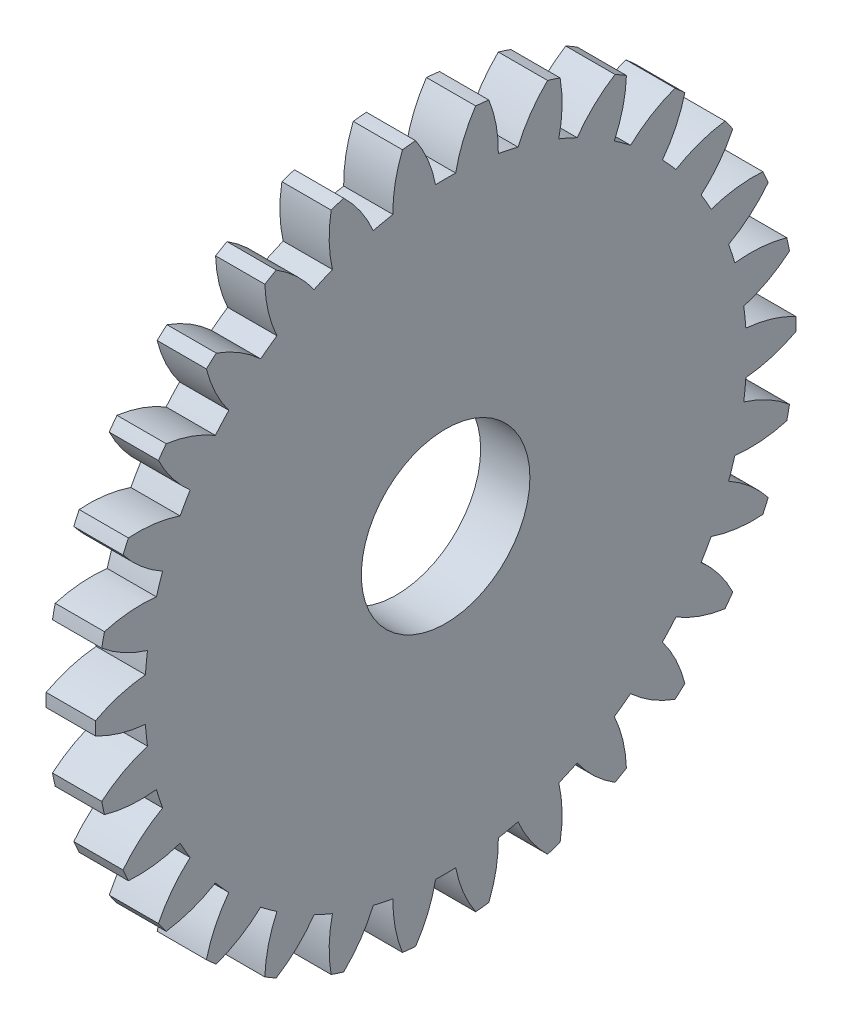
SolidWorks part; units mm, degrees
ref_plane "Plane1" through (0, 0, 0) normal (0, 0, 1) x (1, 0, 0)
ref_plane "Plane2" through (0, 0, 0) normal (0, 1, 0) x (1, 0, 0)
ref_plane "Plane3" through (0, 0, 0) normal (1, 0, 0) x (0, 0, -1)
other "Configuration Table"
sketch "HoldingSke" plane through (0, 0, 0) normal (0, 1, 0) x (1, 0, 0)
  line L0 (0, 0) -> (0.433, -0.25)
  line L1 (-15, 0) -> (100, 0) construction
  line L2 (0, 0) -> (-2.1039, 2.3779)
  line L3 (0, 0) -> (-11.863, 4.5341)
  line L4 (0, 0) -> (7.479, 4.318)
  line L5 (0, 0) -> (-46.8476, -17.4728)
  line L6 (0, 0) -> (-3.7303, -2.5169)
  line L7 (-2.1039, 2.3779) -> (8.6586, 51.2059)
  line L8 (-76.2, 54.61) -> (-74.4, 54.61)
  line L9 (-71.009, 38.7566) -> (-53.1078, 45.2721)
  line L10 (-76.2, 71.12) -> (104.1128, 71.12)
  line L11 (0, 0) -> (-4.5, 0)
  line L12 (-76.2, 101.6) -> (-76.133, 101.6)
  line L13 (24.9733, 27.94) -> (52.9518, 28.4284)
  line L14 (24.9733, 27.94) -> (24.9743, 27.94)
  line L15 (24.9733, 27.94) -> (100.4006, 29.5858)
  line L16 (-63.627, -2) -> (-12.827, -2)
  circle A0 centre (0, 0) radius 5
  circle A1 centre (0, 0) radius 27.499
  circle A2 centre (0, 0) radius 37.5
  circle A3 centre (0, 0) radius 5
  dimension "MHD" = 54.998
  dimension "Hub_dia" = 75
  dimension "Bore" = 10
  dimension "MBD" = 10
  dimension "Num_teeth" = 30
  dimension "Pitch" = 0.5
  dimension "Overall_len" = 50
  dimension "Show_teeth" = 30
  dimension "Thickness" = 4.5
  dimension "OAL" = 50.0001
  dimension "T_dim" = 1.8
  dimension "Ap" = 20
  dimension "H" = 19.05
  dimension "Pitch_radius" = 180.3128
  dimension "Width" = 4.5
  dimension "Backlash" = 0.067
  dimension "Addendum_fac" = 1
  dimension "Dedendum_fac" = 1.25
  dimension "Clearance_fac" = 0.25
  dimension "Dedendum_add" = 0.001
  dimension "Module" = 2
sketch "BasProSke" plane through (0, 0, 0) normal (0, 1, 0) x (1, 0, 0)
  line L0 (-10, 0) -> (60, 0) construction
  line L1 (0, 0) -> (0, 32)
  line L2 (0, 0) -> (4.5, 0)
  line L3 (4.5, 0) -> (4.5, 32)
  line L4 (4.5, 32) -> (0, 32)
  dimension "Thickness" = 4.5
  dimension "Diameter" = 64
revolve "Base-Revolve" add sketch "BasProSke" angle 360 about L0
sketch "TooCutSke" plane through (0, 0, 0) normal (1, 0, 0) x (0, 0, -1)
  line L1 (0, 0) -> (0, 107) construction
  line L2 (0, 0) -> (-1.6873, 29.9525) construction
  line L3 (0, 0) -> (-6.2643, 59.6013) construction
  line L4 (-1.6873, 29.9525) -> (-3.1322, 29.8007) construction
  arc A0 (0.9186, 27.4837) -> (-0.9186, 27.4837) centre (0, 0) ccw
  arc A1 (2.7618, 31.9061) -> (-2.7618, 31.9061) centre (0, 0) ccw
  circle A2 centre (0, 0) radius 30 construction
  circle A3 centre (0, 0) radius 28.1908 construction
  arc A4 (-0.9186, 27.4837) -> (-2.7618, 31.9061) centre (-12.6936, 25.1712) ccw
  arc A5 (2.7618, 31.9061) -> (0.9186, 27.4837) centre (12.6936, 25.1712) ccw
  dimension "Root_dia" = 54.998
  dimension "Overcut_dia" = 64.0508
  dimension "Pitch_dia" = 60
  dimension "Base_dia" = 56.3816
  dimension "Flank_rad" = 12
  dimension "Half_ang" = 6
  dimension "Half_CT" = 1.4528
extrude "ToothCut" cut sketch "TooCutSke" along normal through all
fillet "Breaks" [suppressed] radius 0.04
fillet "RootFillets" [suppressed] radius 0.501
pattern_circular "TeethCuts" count 30 every 12 about axis through (-10, 0, 0) along (1, 0, 0) of "ToothCut", "RootFillets", "Breaks"
sketch "HubNeaOneSke" plane through (0, 0, 0) normal (-1, 0, 0) x (0, 0, 1)
  circle A0 centre (0, 0) radius 27.499
  dimension "Diameter" = 54.998
extrude "HubNearOne" [suppressed] add sketch "HubNeaOneSke" along normal blind 45.5001
sketch "HubNeaBotSke" plane through (0, 0, 0) normal (-1, 0, 0) x (0, 0, 1)
  circle A0 centre (0, 0) radius 27.499
  dimension "Diameter" = 54.998
extrude "HubNearBoth" [suppressed] add sketch "HubNeaBotSke" along normal blind 22.75
ref_plane "FarPln" through (4.5, 0, 0) normal (1, 0, 0) x (0, 0, -1)
sketch "HubFarSke" plane through (4.5, 0, 0) normal (1, 0, 0) x (0, 0, -1)
  circle A0 centre (0, 0) radius 27.499
  dimension "Diameter" = 54.998
extrude "HubFar" [suppressed] add sketch "HubFarSke" along normal blind 22.75
sketch "BorSke" plane through (0, 0, 0) normal (1, 0, 0) x (0, 0, -1)
  circle A0 centre (0, 0) radius 5
  dimension "Diameter" = 10
extrude "Bore" cut sketch "BorSke" along normal mid plane 100.0001
sketch "KeySke" plane through (0, 0, 0) normal (1, 0, 0) x (0, 0, -1)
  line L0 (-2, 0) -> (-2, 6.8)
  line L1 (-2, 6.8) -> (2, 6.8)
  line L2 (2, 6.8) -> (2, 0)
  line L3 (0, 0) -> (0, 34) construction
  line L4 (-2, 0) -> (2, 0)
  dimension "Offset" = 6.8
  dimension "Width" = 4
extrude "Keyway" [suppressed] cut sketch "KeySke" along normal mid plane 100.0001
pattern_circular "Keyway2" [suppressed] count 2 every 90 about axis through (-10, 0, 0) along (1, 0, 0)
sketch "Sketch1" plane through (4.5, 0, 0) normal (1, 0, 0) x (0, 0, -1)
  circle A0 centre (0, 0) radius 7.7
  arc A120 (-31.9943, -0.6021) -> (-27.4291, -1.9593) centre (-26.3602, 9.993) ccw
  arc A121 (-27.4291, -1.9593) -> (-27.2371, -3.7863) centre (0, 0) ccw
  arc A122 (-27.2371, -3.7863) -> (-31.4204, -6.063) centre (-23.7065, -15.2552) ccw
  arc A123 (-31.4204, -6.063) -> (-31.17, -7.241) centre (0, 0) ccw
  arc A124 (-31.17, -7.241) -> (-26.4224, -7.6193) centre (-27.8618, 4.294) ccw
  arc A125 (-26.4224, -7.6193) -> (-25.8547, -9.3665) centre (0, 0) ccw
  arc A126 (-25.8547, -9.3665) -> (-29.4732, -12.4632) centre (-20.0167, -19.8507) ccw
  arc A127 (-29.4732, -12.4632) -> (-28.9834, -13.5633) centre (0, 0) ccw
  arc A128 (-28.9834, -13.5633) -> (-24.2608, -12.9463) centre (-28.1458, -1.5926) ccw
  arc A129 (-24.2608, -12.9463) -> (-23.3423, -14.5373) centre (0, 0) ccw
  arc A130 (-23.3423, -14.5373) -> (-26.2379, -18.3187) centre (-15.4521, -23.5786) ccw
  arc A131 (-26.2379, -18.3187) -> (-25.53, -19.2929) centre (0, 0) ccw
  arc A132 (-25.53, -19.2929) -> (-21.039, -17.7075) centre (-27.1996, -7.4096) ccw
  arc A133 (-21.039, -17.7075) -> (-19.8097, -19.0728) centre (0, 0) ccw
  arc A134 (-19.8097, -19.0728) -> (-21.8559, -23.3735) centre (-10.2122, -26.2761) ccw
  arc A135 (-21.8559, -23.3735) -> (-20.9609, -24.1793) centre (0, 0) ccw
  arc A136 (-20.9609, -24.1793) -> (-16.8976, -21.6948) centre (-25.0647, -12.9028) ccw
  arc A137 (-16.8976, -21.6948) -> (-15.4114, -22.7747) centre (0, 0) ccw
  arc A138 (-15.4114, -22.7747) -> (-16.5186, -27.4068) centre (-4.5259, -27.8251) ccw
  arc A139 (-16.5186, -27.4068) -> (-15.4757, -28.009) centre (0, 0) ccw
  arc A140 (-15.4757, -28.009) -> (-12.0177, -24.734) centre (-21.8343, -17.8321) ccw
  arc A141 (-12.0177, -24.734) -> (-10.3395, -25.4812) centre (0, 0) ccw
  arc A142 (-10.3395, -25.4812) -> (-10.4594, -30.2424) centre (1.3582, -28.158) ccw
  arc A143 (-10.4594, -30.2424) -> (-9.3141, -30.6145) centre (0, 0) ccw
  arc A144 (-9.3141, -30.6145) -> (-6.6127, -26.6921) centre (-17.6497, -21.982) ccw
  arc A145 (-6.6127, -26.6921) -> (-4.8157, -27.074) centre (0, 0) ccw
  arc A146 (-4.8157, -27.074) -> (-3.9431, -31.7561) centre (7.1829, -27.2603) ccw
  arc A147 (-3.9431, -31.7561) -> (-2.7455, -31.882) centre (0, 0) ccw
  arc A148 (-2.7455, -31.882) -> (-0.9186, -27.4837) centre (-12.6936, -25.1712) ccw
  arc A149 (-0.9186, -27.4837) -> (0.9186, -27.4837) centre (0, 0) ccw
  arc A150 (0.9186, -27.4837) -> (2.7455, -31.882) centre (12.6936, -25.1712) ccw
  arc A151 (2.7455, -31.882) -> (3.9431, -31.7561) centre (0, 0) ccw
  arc A152 (3.9431, -31.7561) -> (4.8157, -27.074) centre (-7.1829, -27.2603) ccw
  arc A153 (4.8157, -27.074) -> (6.6127, -26.6921) centre (0, 0) ccw
  arc A154 (6.6127, -26.6921) -> (9.3141, -30.6145) centre (17.6497, -21.982) ccw
  arc A155 (9.3141, -30.6145) -> (10.4594, -30.2424) centre (0, 0) ccw
  arc A156 (10.4594, -30.2424) -> (10.3395, -25.4812) centre (-1.3582, -28.158) ccw
  arc A157 (10.3395, -25.4812) -> (12.0177, -24.734) centre (0, 0) ccw
  arc A158 (12.0177, -24.734) -> (15.4757, -28.009) centre (21.8343, -17.8321) ccw
  arc A159 (15.4757, -28.009) -> (16.5186, -27.4068) centre (0, 0) ccw
  arc A160 (16.5186, -27.4068) -> (15.4114, -22.7747) centre (4.5259, -27.8251) ccw
  arc A161 (15.4114, -22.7747) -> (16.8976, -21.6948) centre (0, 0) ccw
  arc A162 (16.8976, -21.6948) -> (20.9609, -24.1793) centre (25.0647, -12.9028) ccw
  arc A163 (20.9609, -24.1793) -> (21.8559, -23.3735) centre (0, 0) ccw
  arc A164 (21.8559, -23.3735) -> (19.8097, -19.0728) centre (10.2122, -26.2761) ccw
  arc A165 (19.8097, -19.0728) -> (21.039, -17.7075) centre (0, 0) ccw
  arc A166 (21.039, -17.7075) -> (25.53, -19.2929) centre (27.1996, -7.4096) ccw
  arc A167 (25.53, -19.2929) -> (26.2379, -18.3187) centre (0, 0) ccw
  arc A168 (26.2379, -18.3187) -> (23.3423, -14.5373) centre (15.4521, -23.5786) ccw
  arc A169 (23.3423, -14.5373) -> (24.2608, -12.9463) centre (0, 0) ccw
  arc A170 (24.2608, -12.9463) -> (28.9834, -13.5633) centre (28.1458, -1.5926) ccw
  arc A171 (28.9834, -13.5633) -> (29.4732, -12.4632) centre (0, 0) ccw
  arc A172 (29.4732, -12.4632) -> (25.8547, -9.3665) centre (20.0167, -19.8507) ccw
  arc A173 (25.8547, -9.3665) -> (26.4224, -7.6193) centre (0, 0) ccw
  arc A174 (26.4224, -7.6193) -> (31.17, -7.241) centre (27.8618, 4.294) ccw
  arc A175 (31.17, -7.241) -> (31.4204, -6.063) centre (0, 0) ccw
  arc A176 (31.4204, -6.063) -> (27.2371, -3.7863) centre (23.7065, -15.2552) ccw
  arc A177 (27.2371, -3.7863) -> (27.4291, -1.9593) centre (0, 0) ccw
  arc A178 (27.4291, -1.9593) -> (31.9943, -0.6021) centre (26.3602, 9.993) ccw
  arc A179 (31.9943, -0.6021) -> (31.9943, 0.6021) centre (0, 0) ccw
  arc A180 (31.9943, 0.6021) -> (27.4291, 1.9593) centre (26.3602, -9.993) ccw
  arc A181 (27.4291, 1.9593) -> (27.2371, 3.7863) centre (0, 0) ccw
  arc A182 (27.2371, 3.7863) -> (31.4204, 6.063) centre (23.7065, 15.2552) ccw
  arc A183 (31.4204, 6.063) -> (31.17, 7.241) centre (0, 0) ccw
  arc A184 (31.17, 7.241) -> (26.4224, 7.6193) centre (27.8618, -4.294) ccw
  arc A185 (26.4224, 7.6193) -> (25.8547, 9.3665) centre (0, 0) ccw
  arc A186 (25.8547, 9.3665) -> (29.4732, 12.4632) centre (20.0167, 19.8507) ccw
  arc A187 (29.4732, 12.4632) -> (28.9834, 13.5633) centre (0, 0) ccw
  arc A188 (28.9834, 13.5633) -> (24.2608, 12.9463) centre (28.1458, 1.5926) ccw
  arc A189 (24.2608, 12.9463) -> (23.3423, 14.5373) centre (0, 0) ccw
  arc A190 (23.3423, 14.5373) -> (26.2379, 18.3187) centre (15.4521, 23.5786) ccw
  arc A191 (26.2379, 18.3187) -> (25.53, 19.2929) centre (0, 0) ccw
  arc A192 (25.53, 19.2929) -> (21.039, 17.7075) centre (27.1996, 7.4096) ccw
  arc A193 (21.039, 17.7075) -> (19.8097, 19.0728) centre (0, 0) ccw
  arc A194 (19.8097, 19.0728) -> (21.8559, 23.3735) centre (10.2122, 26.2761) ccw
  arc A195 (21.8559, 23.3735) -> (20.9609, 24.1793) centre (0, 0) ccw
  arc A196 (20.9609, 24.1793) -> (16.8976, 21.6948) centre (25.0647, 12.9028) ccw
  arc A197 (16.8976, 21.6948) -> (15.4114, 22.7747) centre (0, 0) ccw
  arc A198 (15.4114, 22.7747) -> (16.5186, 27.4068) centre (4.5259, 27.8251) ccw
  arc A199 (16.5186, 27.4068) -> (15.4757, 28.009) centre (0, 0) ccw
  arc A200 (15.4757, 28.009) -> (12.0177, 24.734) centre (21.8343, 17.8321) ccw
  arc A201 (12.0177, 24.734) -> (10.3395, 25.4812) centre (0, 0) ccw
  arc A202 (10.3395, 25.4812) -> (10.4594, 30.2424) centre (-1.3582, 28.158) ccw
  arc A203 (10.4594, 30.2424) -> (9.3141, 30.6145) centre (0, 0) ccw
  arc A204 (9.3141, 30.6145) -> (6.6127, 26.6921) centre (17.6497, 21.982) ccw
  arc A205 (6.6127, 26.6921) -> (4.8157, 27.074) centre (0, 0) ccw
  arc A206 (4.8157, 27.074) -> (3.9431, 31.7561) centre (-7.1829, 27.2603) ccw
  arc A207 (3.9431, 31.7561) -> (2.7455, 31.882) centre (0, 0) ccw
  arc A208 (2.7455, 31.882) -> (0.9186, 27.4837) centre (12.6936, 25.1712) ccw
  arc A209 (0.9186, 27.4837) -> (-0.9186, 27.4837) centre (0, 0) ccw
  arc A210 (-0.9186, 27.4837) -> (-2.7455, 31.882) centre (-12.6936, 25.1712) ccw
  arc A211 (-2.7455, 31.882) -> (-3.9431, 31.7561) centre (0, 0) ccw
  arc A212 (-3.9431, 31.7561) -> (-4.8157, 27.074) centre (7.1829, 27.2603) ccw
  arc A213 (-4.8157, 27.074) -> (-6.6127, 26.6921) centre (0, 0) ccw
  arc A214 (-6.6127, 26.6921) -> (-9.3141, 30.6145) centre (-17.6497, 21.982) ccw
  arc A215 (-9.3141, 30.6145) -> (-10.4594, 30.2424) centre (0, 0) ccw
  arc A216 (-10.4594, 30.2424) -> (-10.3395, 25.4812) centre (1.3582, 28.158) ccw
  arc A217 (-10.3395, 25.4812) -> (-12.0177, 24.734) centre (0, 0) ccw
  arc A218 (-12.0177, 24.734) -> (-15.4757, 28.009) centre (-21.8343, 17.8321) ccw
  arc A219 (-15.4757, 28.009) -> (-16.5186, 27.4068) centre (0, 0) ccw
  arc A220 (-16.5186, 27.4068) -> (-15.4114, 22.7747) centre (-4.5259, 27.8251) ccw
  arc A221 (-15.4114, 22.7747) -> (-16.8976, 21.6948) centre (0, 0) ccw
  arc A222 (-16.8976, 21.6948) -> (-20.9609, 24.1793) centre (-25.0647, 12.9028) ccw
  arc A223 (-20.9609, 24.1793) -> (-21.8559, 23.3735) centre (0, 0) ccw
  arc A224 (-21.8559, 23.3735) -> (-19.8097, 19.0728) centre (-10.2122, 26.2761) ccw
  arc A225 (-19.8097, 19.0728) -> (-21.039, 17.7075) centre (0, 0) ccw
  arc A226 (-21.039, 17.7075) -> (-25.53, 19.2929) centre (-27.1996, 7.4096) ccw
  arc A227 (-25.53, 19.2929) -> (-26.2379, 18.3187) centre (0, 0) ccw
  arc A228 (-26.2379, 18.3187) -> (-23.3423, 14.5373) centre (-15.4521, 23.5786) ccw
  arc A229 (-23.3423, 14.5373) -> (-24.2608, 12.9463) centre (0, 0) ccw
  arc A230 (-24.2608, 12.9463) -> (-28.9834, 13.5633) centre (-28.1458, 1.5926) ccw
  arc A231 (-28.9834, 13.5633) -> (-29.4732, 12.4632) centre (0, 0) ccw
  arc A232 (-29.4732, 12.4632) -> (-25.8547, 9.3665) centre (-20.0167, 19.8507) ccw
  arc A233 (-25.8547, 9.3665) -> (-26.4224, 7.6193) centre (0, 0) ccw
  arc A234 (-26.4224, 7.6193) -> (-31.17, 7.241) centre (-27.8618, -4.294) ccw
  arc A235 (-31.17, 7.241) -> (-31.4204, 6.063) centre (0, 0) ccw
  arc A236 (-31.4204, 6.063) -> (-27.2371, 3.7863) centre (-23.7065, 15.2552) ccw
  arc A237 (-27.2371, 3.7863) -> (-27.4291, 1.9593) centre (0, 0) ccw
  arc A238 (-27.4291, 1.9593) -> (-31.9943, 0.6021) centre (-26.3602, -9.993) ccw
  arc A239 (-31.9943, 0.6021) -> (-31.9943, -0.6021) centre (0, 0) ccw
  arc A240 (-31.9943, -0.6021) -> (-27.4291, -1.9593) centre (-26.3602, 9.993) ccw
  arc A241 (-27.4291, -1.9593) -> (-27.2371, -3.7863) centre (0, 0) ccw
  arc A242 (-27.2371, -3.7863) -> (-31.4204, -6.063) centre (-23.7065, -15.2552) ccw
  arc A243 (-31.4204, -6.063) -> (-31.17, -7.241) centre (0, 0) ccw
  arc A244 (-31.17, -7.241) -> (-26.4224, -7.6193) centre (-27.8618, 4.294) ccw
  arc A245 (-26.4224, -7.6193) -> (-25.8547, -9.3665) centre (0, 0) ccw
  arc A246 (-25.8547, -9.3665) -> (-29.4732, -12.4632) centre (-20.0167, -19.8507) ccw
  arc A247 (-29.4732, -12.4632) -> (-28.9834, -13.5633) centre (0, 0) ccw
  arc A248 (-28.9834, -13.5633) -> (-24.2608, -12.9463) centre (-28.1458, -1.5926) ccw
  arc A249 (-24.2608, -12.9463) -> (-23.3423, -14.5373) centre (0, 0) ccw
  arc A250 (-23.3423, -14.5373) -> (-26.2379, -18.3187) centre (-15.4521, -23.5786) ccw
  arc A251 (-26.2379, -18.3187) -> (-25.53, -19.2929) centre (0, 0) ccw
  arc A252 (-25.53, -19.2929) -> (-21.039, -17.7075) centre (-27.1996, -7.4096) ccw
  arc A253 (-21.039, -17.7075) -> (-19.8097, -19.0728) centre (0, 0) ccw
  arc A254 (-19.8097, -19.0728) -> (-21.8559, -23.3735) centre (-10.2122, -26.2761) ccw
  arc A255 (-21.8559, -23.3735) -> (-20.9609, -24.1793) centre (0, 0) ccw
  arc A256 (-20.9609, -24.1793) -> (-16.8976, -21.6948) centre (-25.0647, -12.9028) ccw
  arc A257 (-16.8976, -21.6948) -> (-15.4114, -22.7747) centre (0, 0) ccw
  arc A258 (-15.4114, -22.7747) -> (-16.5186, -27.4068) centre (-4.5259, -27.8251) ccw
  arc A259 (-16.5186, -27.4068) -> (-15.4757, -28.009) centre (0, 0) ccw
  arc A260 (-15.4757, -28.009) -> (-12.0177, -24.734) centre (-21.8343, -17.8321) ccw
  arc A261 (-12.0177, -24.734) -> (-10.3395, -25.4812) centre (0, 0) ccw
  arc A262 (-10.3395, -25.4812) -> (-10.4594, -30.2424) centre (1.3582, -28.158) ccw
  arc A263 (-10.4594, -30.2424) -> (-9.3141, -30.6145) centre (0, 0) ccw
  arc A264 (-9.3141, -30.6145) -> (-6.6127, -26.6921) centre (-17.6497, -21.982) ccw
  arc A265 (-6.6127, -26.6921) -> (-4.8157, -27.074) centre (0, 0) ccw
  arc A266 (-4.8157, -27.074) -> (-3.9431, -31.7561) centre (7.1829, -27.2603) ccw
  arc A267 (-3.9431, -31.7561) -> (-2.7455, -31.882) centre (0, 0) ccw
  arc A268 (-2.7455, -31.882) -> (-0.9186, -27.4837) centre (-12.6936, -25.1712) ccw
  arc A269 (-0.9186, -27.4837) -> (0.9186, -27.4837) centre (0, 0) ccw
  arc A270 (0.9186, -27.4837) -> (2.7455, -31.882) centre (12.6936, -25.1712) ccw
  arc A271 (2.7455, -31.882) -> (3.9431, -31.7561) centre (0, 0) ccw
  arc A272 (3.9431, -31.7561) -> (4.8157, -27.074) centre (-7.1829, -27.2603) ccw
  arc A273 (4.8157, -27.074) -> (6.6127, -26.6921) centre (0, 0) ccw
  arc A274 (6.6127, -26.6921) -> (9.3141, -30.6145) centre (17.6497, -21.982) ccw
  arc A275 (9.3141, -30.6145) -> (10.4594, -30.2424) centre (0, 0) ccw
  arc A276 (10.4594, -30.2424) -> (10.3395, -25.4812) centre (-1.3582, -28.158) ccw
  arc A277 (10.3395, -25.4812) -> (12.0177, -24.734) centre (0, 0) ccw
  arc A278 (12.0177, -24.734) -> (15.4757, -28.009) centre (21.8343, -17.8321) ccw
  arc A279 (15.4757, -28.009) -> (16.5186, -27.4068) centre (0, 0) ccw
  arc A280 (16.5186, -27.4068) -> (15.4114, -22.7747) centre (4.5259, -27.8251) ccw
  arc A281 (15.4114, -22.7747) -> (16.8976, -21.6948) centre (0, 0) ccw
  arc A282 (16.8976, -21.6948) -> (20.9609, -24.1793) centre (25.0647, -12.9028) ccw
  arc A283 (20.9609, -24.1793) -> (21.8559, -23.3735) centre (0, 0) ccw
  arc A284 (21.8559, -23.3735) -> (19.8097, -19.0728) centre (10.2122, -26.2761) ccw
  arc A285 (19.8097, -19.0728) -> (21.039, -17.7075) centre (0, 0) ccw
  arc A286 (21.039, -17.7075) -> (25.53, -19.2929) centre (27.1996, -7.4096) ccw
  arc A287 (25.53, -19.2929) -> (26.2379, -18.3187) centre (0, 0) ccw
  arc A288 (26.2379, -18.3187) -> (23.3423, -14.5373) centre (15.4521, -23.5786) ccw
  arc A289 (23.3423, -14.5373) -> (24.2608, -12.9463) centre (0, 0) ccw
  arc A290 (24.2608, -12.9463) -> (28.9834, -13.5633) centre (28.1458, -1.5926) ccw
  arc A291 (28.9834, -13.5633) -> (29.4732, -12.4632) centre (0, 0) ccw
  arc A292 (29.4732, -12.4632) -> (25.8547, -9.3665) centre (20.0167, -19.8507) ccw
  arc A293 (25.8547, -9.3665) -> (26.4224, -7.6193) centre (0, 0) ccw
  arc A294 (26.4224, -7.6193) -> (31.17, -7.241) centre (27.8618, 4.294) ccw
  arc A295 (31.17, -7.241) -> (31.4204, -6.063) centre (0, 0) ccw
  arc A296 (31.4204, -6.063) -> (27.2371, -3.7863) centre (23.7065, -15.2552) ccw
  arc A297 (27.2371, -3.7863) -> (27.4291, -1.9593) centre (0, 0) ccw
  arc A298 (27.4291, -1.9593) -> (31.9943, -0.6021) centre (26.3602, 9.993) ccw
  arc A299 (31.9943, -0.6021) -> (31.9943, 0.6021) centre (0, 0) ccw
  arc A300 (31.9943, 0.6021) -> (27.4291, 1.9593) centre (26.3602, -9.993) ccw
  arc A301 (27.4291, 1.9593) -> (27.2371, 3.7863) centre (0, 0) ccw
  arc A302 (27.2371, 3.7863) -> (31.4204, 6.063) centre (23.7065, 15.2552) ccw
  arc A303 (31.4204, 6.063) -> (31.17, 7.241) centre (0, 0) ccw
  arc A304 (31.17, 7.241) -> (26.4224, 7.6193) centre (27.8618, -4.294) ccw
  arc A305 (26.4224, 7.6193) -> (25.8547, 9.3665) centre (0, 0) ccw
  arc A306 (25.8547, 9.3665) -> (29.4732, 12.4632) centre (20.0167, 19.8507) ccw
  arc A307 (29.4732, 12.4632) -> (28.9834, 13.5633) centre (0, 0) ccw
  arc A308 (28.9834, 13.5633) -> (24.2608, 12.9463) centre (28.1458, 1.5926) ccw
  arc A309 (24.2608, 12.9463) -> (23.3423, 14.5373) centre (0, 0) ccw
  arc A310 (23.3423, 14.5373) -> (26.2379, 18.3187) centre (15.4521, 23.5786) ccw
  arc A311 (26.2379, 18.3187) -> (25.53, 19.2929) centre (0, 0) ccw
  arc A312 (25.53, 19.2929) -> (21.039, 17.7075) centre (27.1996, 7.4096) ccw
  arc A313 (21.039, 17.7075) -> (19.8097, 19.0728) centre (0, 0) ccw
  arc A314 (19.8097, 19.0728) -> (21.8559, 23.3735) centre (10.2122, 26.2761) ccw
  arc A315 (21.8559, 23.3735) -> (20.9609, 24.1793) centre (0, 0) ccw
  arc A316 (20.9609, 24.1793) -> (16.8976, 21.6948) centre (25.0647, 12.9028) ccw
  arc A317 (16.8976, 21.6948) -> (15.4114, 22.7747) centre (0, 0) ccw
  arc A318 (15.4114, 22.7747) -> (16.5186, 27.4068) centre (4.5259, 27.8251) ccw
  arc A319 (16.5186, 27.4068) -> (15.4757, 28.009) centre (0, 0) ccw
  arc A320 (15.4757, 28.009) -> (12.0177, 24.734) centre (21.8343, 17.8321) ccw
  arc A321 (12.0177, 24.734) -> (10.3395, 25.4812) centre (0, 0) ccw
  arc A322 (10.3395, 25.4812) -> (10.4594, 30.2424) centre (-1.3582, 28.158) ccw
  arc A323 (10.4594, 30.2424) -> (9.3141, 30.6145) centre (0, 0) ccw
  arc A324 (9.3141, 30.6145) -> (6.6127, 26.6921) centre (17.6497, 21.982) ccw
  arc A325 (6.6127, 26.6921) -> (4.8157, 27.074) centre (0, 0) ccw
  arc A326 (4.8157, 27.074) -> (3.9431, 31.7561) centre (-7.1829, 27.2603) ccw
  arc A327 (3.9431, 31.7561) -> (2.7455, 31.882) centre (0, 0) ccw
  arc A328 (2.7455, 31.882) -> (0.9186, 27.4837) centre (12.6936, 25.1712) ccw
  arc A329 (0.9186, 27.4837) -> (-0.9186, 27.4837) centre (0, 0) ccw
  arc A330 (-0.9186, 27.4837) -> (-2.7455, 31.882) centre (-12.6936, 25.1712) ccw
  arc A331 (-2.7455, 31.882) -> (-3.9431, 31.7561) centre (0, 0) ccw
  arc A332 (-3.9431, 31.7561) -> (-4.8157, 27.074) centre (7.1829, 27.2603) ccw
  arc A333 (-4.8157, 27.074) -> (-6.6127, 26.6921) centre (0, 0) ccw
  arc A334 (-6.6127, 26.6921) -> (-9.3141, 30.6145) centre (-17.6497, 21.982) ccw
  arc A335 (-9.3141, 30.6145) -> (-10.4594, 30.2424) centre (0, 0) ccw
  arc A336 (-10.4594, 30.2424) -> (-10.3395, 25.4812) centre (1.3582, 28.158) ccw
  arc A337 (-10.3395, 25.4812) -> (-12.0177, 24.734) centre (0, 0) ccw
  arc A338 (-12.0177, 24.734) -> (-15.4757, 28.009) centre (-21.8343, 17.8321) ccw
  arc A339 (-15.4757, 28.009) -> (-16.5186, 27.4068) centre (0, 0) ccw
  arc A340 (-16.5186, 27.4068) -> (-15.4114, 22.7747) centre (-4.5259, 27.8251) ccw
  arc A341 (-15.4114, 22.7747) -> (-16.8976, 21.6948) centre (0, 0) ccw
  arc A342 (-16.8976, 21.6948) -> (-20.9609, 24.1793) centre (-25.0647, 12.9028) ccw
  arc A343 (-20.9609, 24.1793) -> (-21.8559, 23.3735) centre (0, 0) ccw
  arc A344 (-21.8559, 23.3735) -> (-19.8097, 19.0728) centre (-10.2122, 26.2761) ccw
  arc A345 (-19.8097, 19.0728) -> (-21.039, 17.7075) centre (0, 0) ccw
  arc A346 (-21.039, 17.7075) -> (-25.53, 19.2929) centre (-27.1996, 7.4096) ccw
  arc A347 (-25.53, 19.2929) -> (-26.2379, 18.3187) centre (0, 0) ccw
  arc A348 (-26.2379, 18.3187) -> (-23.3423, 14.5373) centre (-15.4521, 23.5786) ccw
  arc A349 (-23.3423, 14.5373) -> (-24.2608, 12.9463) centre (0, 0) ccw
  arc A350 (-24.2608, 12.9463) -> (-28.9834, 13.5633) centre (-28.1458, 1.5926) ccw
  arc A351 (-28.9834, 13.5633) -> (-29.4732, 12.4632) centre (0, 0) ccw
  arc A352 (-29.4732, 12.4632) -> (-25.8547, 9.3665) centre (-20.0167, 19.8507) ccw
  arc A353 (-25.8547, 9.3665) -> (-26.4224, 7.6193) centre (0, 0) ccw
  arc A354 (-26.4224, 7.6193) -> (-31.17, 7.241) centre (-27.8618, -4.294) ccw
  arc A355 (-31.17, 7.241) -> (-31.4204, 6.063) centre (0, 0) ccw
  arc A356 (-31.4204, 6.063) -> (-27.2371, 3.7863) centre (-23.7065, 15.2552) ccw
  arc A357 (-27.2371, 3.7863) -> (-27.4291, 1.9593) centre (0, 0) ccw
  arc A358 (-27.4291, 1.9593) -> (-31.9943, 0.6021) centre (-26.3602, -9.993) ccw
  arc A359 (-31.9943, 0.6021) -> (-31.9943, -0.6021) centre (0, 0) ccw
  dimension "D2" = 15.4
  dimension "D1" = 0
extrude "Cut-Extrude1" cut sketch "Sketch1" against normal through all contours A0
sketch "Sketch2" plane through (4.5, 0, 0) normal (1, 0, 0) x (0, 0, -1)
  line L0 (-25, 25) -> (25, -25) construction
  line L1 (-25, 25) -> (25, 25)
  line L2 (-25, 25) -> (-25, -25)
  line L3 (-25, -25) -> (25, -25)
  line L4 (25, 25) -> (25, -25)
  arc A120 (-31.9943, -0.6021) -> (-27.4291, -1.9593) centre (-26.3602, 9.993) ccw
  arc A121 (-27.4291, -1.9593) -> (-27.2371, -3.7863) centre (0, 0) ccw
  arc A122 (-27.2371, -3.7863) -> (-31.4204, -6.063) centre (-23.7065, -15.2552) ccw
  arc A123 (-31.4204, -6.063) -> (-31.17, -7.241) centre (0, 0) ccw
  arc A124 (-31.17, -7.241) -> (-26.4224, -7.6193) centre (-27.8618, 4.294) ccw
  arc A125 (-26.4224, -7.6193) -> (-25.8547, -9.3665) centre (0, 0) ccw
  arc A126 (-25.8547, -9.3665) -> (-29.4732, -12.4632) centre (-20.0167, -19.8507) ccw
  arc A127 (-29.4732, -12.4632) -> (-28.9834, -13.5633) centre (0, 0) ccw
  arc A128 (-28.9834, -13.5633) -> (-24.2608, -12.9463) centre (-28.1458, -1.5926) ccw
  arc A129 (-24.2608, -12.9463) -> (-23.3423, -14.5373) centre (0, 0) ccw
  arc A130 (-23.3423, -14.5373) -> (-26.2379, -18.3187) centre (-15.4521, -23.5786) ccw
  arc A131 (-26.2379, -18.3187) -> (-25.53, -19.2929) centre (0, 0) ccw
  arc A132 (-25.53, -19.2929) -> (-21.039, -17.7075) centre (-27.1996, -7.4096) ccw
  arc A133 (-21.039, -17.7075) -> (-19.8097, -19.0728) centre (0, 0) ccw
  arc A134 (-19.8097, -19.0728) -> (-21.8559, -23.3735) centre (-10.2122, -26.2761) ccw
  arc A135 (-21.8559, -23.3735) -> (-20.9609, -24.1793) centre (0, 0) ccw
  arc A136 (-20.9609, -24.1793) -> (-16.8976, -21.6948) centre (-25.0647, -12.9028) ccw
  arc A137 (-16.8976, -21.6948) -> (-15.4114, -22.7747) centre (0, 0) ccw
  arc A138 (-15.4114, -22.7747) -> (-16.5186, -27.4068) centre (-4.5259, -27.8251) ccw
  arc A139 (-16.5186, -27.4068) -> (-15.4757, -28.009) centre (0, 0) ccw
  arc A140 (-15.4757, -28.009) -> (-12.0177, -24.734) centre (-21.8343, -17.8321) ccw
  arc A141 (-12.0177, -24.734) -> (-10.3395, -25.4812) centre (0, 0) ccw
  arc A142 (-10.3395, -25.4812) -> (-10.4594, -30.2424) centre (1.3582, -28.158) ccw
  arc A143 (-10.4594, -30.2424) -> (-9.3141, -30.6145) centre (0, 0) ccw
  arc A144 (-9.3141, -30.6145) -> (-6.6127, -26.6921) centre (-17.6497, -21.982) ccw
  arc A145 (-6.6127, -26.6921) -> (-4.8157, -27.074) centre (0, 0) ccw
  arc A146 (-4.8157, -27.074) -> (-3.9431, -31.7561) centre (7.1829, -27.2603) ccw
  arc A147 (-3.9431, -31.7561) -> (-2.7455, -31.882) centre (0, 0) ccw
  arc A148 (-2.7455, -31.882) -> (-0.9186, -27.4837) centre (-12.6936, -25.1712) ccw
  arc A149 (-0.9186, -27.4837) -> (0.9186, -27.4837) centre (0, 0) ccw
  arc A150 (0.9186, -27.4837) -> (2.7455, -31.882) centre (12.6936, -25.1712) ccw
  arc A151 (2.7455, -31.882) -> (3.9431, -31.7561) centre (0, 0) ccw
  arc A152 (3.9431, -31.7561) -> (4.8157, -27.074) centre (-7.1829, -27.2603) ccw
  arc A153 (4.8157, -27.074) -> (6.6127, -26.6921) centre (0, 0) ccw
  arc A154 (6.6127, -26.6921) -> (9.3141, -30.6145) centre (17.6497, -21.982) ccw
  arc A155 (9.3141, -30.6145) -> (10.4594, -30.2424) centre (0, 0) ccw
  arc A156 (10.4594, -30.2424) -> (10.3395, -25.4812) centre (-1.3582, -28.158) ccw
  arc A157 (10.3395, -25.4812) -> (12.0177, -24.734) centre (0, 0) ccw
  arc A158 (12.0177, -24.734) -> (15.4757, -28.009) centre (21.8343, -17.8321) ccw
  arc A159 (15.4757, -28.009) -> (16.5186, -27.4068) centre (0, 0) ccw
  arc A160 (16.5186, -27.4068) -> (15.4114, -22.7747) centre (4.5259, -27.8251) ccw
  arc A161 (15.4114, -22.7747) -> (16.8976, -21.6948) centre (0, 0) ccw
  arc A162 (16.8976, -21.6948) -> (20.9609, -24.1793) centre (25.0647, -12.9028) ccw
  arc A163 (20.9609, -24.1793) -> (21.8559, -23.3735) centre (0, 0) ccw
  arc A164 (21.8559, -23.3735) -> (19.8097, -19.0728) centre (10.2122, -26.2761) ccw
  arc A165 (19.8097, -19.0728) -> (21.039, -17.7075) centre (0, 0) ccw
  arc A166 (21.039, -17.7075) -> (25.53, -19.2929) centre (27.1996, -7.4096) ccw
  arc A167 (25.53, -19.2929) -> (26.2379, -18.3187) centre (0, 0) ccw
  arc A168 (26.2379, -18.3187) -> (23.3423, -14.5373) centre (15.4521, -23.5786) ccw
  arc A169 (23.3423, -14.5373) -> (24.2608, -12.9463) centre (0, 0) ccw
  arc A170 (24.2608, -12.9463) -> (28.9834, -13.5633) centre (28.1458, -1.5926) ccw
  arc A171 (28.9834, -13.5633) -> (29.4732, -12.4632) centre (0, 0) ccw
  arc A172 (29.4732, -12.4632) -> (25.8547, -9.3665) centre (20.0167, -19.8507) ccw
  arc A173 (25.8547, -9.3665) -> (26.4224, -7.6193) centre (0, 0) ccw
  arc A174 (26.4224, -7.6193) -> (31.17, -7.241) centre (27.8618, 4.294) ccw
  arc A175 (31.17, -7.241) -> (31.4204, -6.063) centre (0, 0) ccw
  arc A176 (31.4204, -6.063) -> (27.2371, -3.7863) centre (23.7065, -15.2552) ccw
  arc A177 (27.2371, -3.7863) -> (27.4291, -1.9593) centre (0, 0) ccw
  arc A178 (27.4291, -1.9593) -> (31.9943, -0.6021) centre (26.3602, 9.993) ccw
  arc A179 (31.9943, -0.6021) -> (31.9943, 0.6021) centre (0, 0) ccw
  arc A180 (31.9943, 0.6021) -> (27.4291, 1.9593) centre (26.3602, -9.993) ccw
  arc A181 (27.4291, 1.9593) -> (27.2371, 3.7863) centre (0, 0) ccw
  arc A182 (27.2371, 3.7863) -> (31.4204, 6.063) centre (23.7065, 15.2552) ccw
  arc A183 (31.4204, 6.063) -> (31.17, 7.241) centre (0, 0) ccw
  arc A184 (31.17, 7.241) -> (26.4224, 7.6193) centre (27.8618, -4.294) ccw
  arc A185 (26.4224, 7.6193) -> (25.8547, 9.3665) centre (0, 0) ccw
  arc A186 (25.8547, 9.3665) -> (29.4732, 12.4632) centre (20.0167, 19.8507) ccw
  arc A187 (29.4732, 12.4632) -> (28.9834, 13.5633) centre (0, 0) ccw
  arc A188 (28.9834, 13.5633) -> (24.2608, 12.9463) centre (28.1458, 1.5926) ccw
  arc A189 (24.2608, 12.9463) -> (23.3423, 14.5373) centre (0, 0) ccw
  arc A190 (23.3423, 14.5373) -> (26.2379, 18.3187) centre (15.4521, 23.5786) ccw
  arc A191 (26.2379, 18.3187) -> (25.53, 19.2929) centre (0, 0) ccw
  arc A192 (25.53, 19.2929) -> (21.039, 17.7075) centre (27.1996, 7.4096) ccw
  arc A193 (21.039, 17.7075) -> (19.8097, 19.0728) centre (0, 0) ccw
  arc A194 (19.8097, 19.0728) -> (21.8559, 23.3735) centre (10.2122, 26.2761) ccw
  arc A195 (21.8559, 23.3735) -> (20.9609, 24.1793) centre (0, 0) ccw
  arc A196 (20.9609, 24.1793) -> (16.8976, 21.6948) centre (25.0647, 12.9028) ccw
  arc A197 (16.8976, 21.6948) -> (15.4114, 22.7747) centre (0, 0) ccw
  arc A198 (15.4114, 22.7747) -> (16.5186, 27.4068) centre (4.5259, 27.8251) ccw
  arc A199 (16.5186, 27.4068) -> (15.4757, 28.009) centre (0, 0) ccw
  arc A200 (15.4757, 28.009) -> (12.0177, 24.734) centre (21.8343, 17.8321) ccw
  arc A201 (12.0177, 24.734) -> (10.3395, 25.4812) centre (0, 0) ccw
  arc A202 (10.3395, 25.4812) -> (10.4594, 30.2424) centre (-1.3582, 28.158) ccw
  arc A203 (10.4594, 30.2424) -> (9.3141, 30.6145) centre (0, 0) ccw
  arc A204 (9.3141, 30.6145) -> (6.6127, 26.6921) centre (17.6497, 21.982) ccw
  arc A205 (6.6127, 26.6921) -> (4.8157, 27.074) centre (0, 0) ccw
  arc A206 (4.8157, 27.074) -> (3.9431, 31.7561) centre (-7.1829, 27.2603) ccw
  arc A207 (3.9431, 31.7561) -> (2.7455, 31.882) centre (0, 0) ccw
  arc A208 (2.7455, 31.882) -> (0.9186, 27.4837) centre (12.6936, 25.1712) ccw
  arc A209 (0.9186, 27.4837) -> (-0.9186, 27.4837) centre (0, 0) ccw
  arc A210 (-0.9186, 27.4837) -> (-2.7455, 31.882) centre (-12.6936, 25.1712) ccw
  arc A211 (-2.7455, 31.882) -> (-3.9431, 31.7561) centre (0, 0) ccw
  arc A212 (-3.9431, 31.7561) -> (-4.8157, 27.074) centre (7.1829, 27.2603) ccw
  arc A213 (-4.8157, 27.074) -> (-6.6127, 26.6921) centre (0, 0) ccw
  arc A214 (-6.6127, 26.6921) -> (-9.3141, 30.6145) centre (-17.6497, 21.982) ccw
  arc A215 (-9.3141, 30.6145) -> (-10.4594, 30.2424) centre (0, 0) ccw
  arc A216 (-10.4594, 30.2424) -> (-10.3395, 25.4812) centre (1.3582, 28.158) ccw
  arc A217 (-10.3395, 25.4812) -> (-12.0177, 24.734) centre (0, 0) ccw
  arc A218 (-12.0177, 24.734) -> (-15.4757, 28.009) centre (-21.8343, 17.8321) ccw
  arc A219 (-15.4757, 28.009) -> (-16.5186, 27.4068) centre (0, 0) ccw
  arc A220 (-16.5186, 27.4068) -> (-15.4114, 22.7747) centre (-4.5259, 27.8251) ccw
  arc A221 (-15.4114, 22.7747) -> (-16.8976, 21.6948) centre (0, 0) ccw
  arc A222 (-16.8976, 21.6948) -> (-20.9609, 24.1793) centre (-25.0647, 12.9028) ccw
  arc A223 (-20.9609, 24.1793) -> (-21.8559, 23.3735) centre (0, 0) ccw
  arc A224 (-21.8559, 23.3735) -> (-19.8097, 19.0728) centre (-10.2122, 26.2761) ccw
  arc A225 (-19.8097, 19.0728) -> (-21.039, 17.7075) centre (0, 0) ccw
  arc A226 (-21.039, 17.7075) -> (-25.53, 19.2929) centre (-27.1996, 7.4096) ccw
  arc A227 (-25.53, 19.2929) -> (-26.2379, 18.3187) centre (0, 0) ccw
  arc A228 (-26.2379, 18.3187) -> (-23.3423, 14.5373) centre (-15.4521, 23.5786) ccw
  arc A229 (-23.3423, 14.5373) -> (-24.2608, 12.9463) centre (0, 0) ccw
  arc A230 (-24.2608, 12.9463) -> (-28.9834, 13.5633) centre (-28.1458, 1.5926) ccw
  arc A231 (-28.9834, 13.5633) -> (-29.4732, 12.4632) centre (0, 0) ccw
  arc A232 (-29.4732, 12.4632) -> (-25.8547, 9.3665) centre (-20.0167, 19.8507) ccw
  arc A233 (-25.8547, 9.3665) -> (-26.4224, 7.6193) centre (0, 0) ccw
  arc A234 (-26.4224, 7.6193) -> (-31.17, 7.241) centre (-27.8618, -4.294) ccw
  arc A235 (-31.17, 7.241) -> (-31.4204, 6.063) centre (0, 0) ccw
  arc A236 (-31.4204, 6.063) -> (-27.2371, 3.7863) centre (-23.7065, 15.2552) ccw
  arc A237 (-27.2371, 3.7863) -> (-27.4291, 1.9593) centre (0, 0) ccw
  arc A238 (-27.4291, 1.9593) -> (-31.9943, 0.6021) centre (-26.3602, -9.993) ccw
  arc A239 (-31.9943, 0.6021) -> (-31.9943, -0.6021) centre (0, 0) ccw
  arc A240 (-31.9943, -0.6021) -> (-27.4291, -1.9593) centre (-26.3602, 9.993) ccw
  arc A241 (-27.4291, -1.9593) -> (-27.2371, -3.7863) centre (0, 0) ccw
  arc A242 (-27.2371, -3.7863) -> (-31.4204, -6.063) centre (-23.7065, -15.2552) ccw
  arc A243 (-31.4204, -6.063) -> (-31.17, -7.241) centre (0, 0) ccw
  arc A244 (-31.17, -7.241) -> (-26.4224, -7.6193) centre (-27.8618, 4.294) ccw
  arc A245 (-26.4224, -7.6193) -> (-25.8547, -9.3665) centre (0, 0) ccw
  arc A246 (-25.8547, -9.3665) -> (-29.4732, -12.4632) centre (-20.0167, -19.8507) ccw
  arc A247 (-29.4732, -12.4632) -> (-28.9834, -13.5633) centre (0, 0) ccw
  arc A248 (-28.9834, -13.5633) -> (-24.2608, -12.9463) centre (-28.1458, -1.5926) ccw
  arc A249 (-24.2608, -12.9463) -> (-23.3423, -14.5373) centre (0, 0) ccw
  arc A250 (-23.3423, -14.5373) -> (-26.2379, -18.3187) centre (-15.4521, -23.5786) ccw
  arc A251 (-26.2379, -18.3187) -> (-25.53, -19.2929) centre (0, 0) ccw
  arc A252 (-25.53, -19.2929) -> (-21.039, -17.7075) centre (-27.1996, -7.4096) ccw
  arc A253 (-21.039, -17.7075) -> (-19.8097, -19.0728) centre (0, 0) ccw
  arc A254 (-19.8097, -19.0728) -> (-21.8559, -23.3735) centre (-10.2122, -26.2761) ccw
  arc A255 (-21.8559, -23.3735) -> (-20.9609, -24.1793) centre (0, 0) ccw
  arc A256 (-20.9609, -24.1793) -> (-16.8976, -21.6948) centre (-25.0647, -12.9028) ccw
  arc A257 (-16.8976, -21.6948) -> (-15.4114, -22.7747) centre (0, 0) ccw
  arc A258 (-15.4114, -22.7747) -> (-16.5186, -27.4068) centre (-4.5259, -27.8251) ccw
  arc A259 (-16.5186, -27.4068) -> (-15.4757, -28.009) centre (0, 0) ccw
  arc A260 (-15.4757, -28.009) -> (-12.0177, -24.734) centre (-21.8343, -17.8321) ccw
  arc A261 (-12.0177, -24.734) -> (-10.3395, -25.4812) centre (0, 0) ccw
  arc A262 (-10.3395, -25.4812) -> (-10.4594, -30.2424) centre (1.3582, -28.158) ccw
  arc A263 (-10.4594, -30.2424) -> (-9.3141, -30.6145) centre (0, 0) ccw
  arc A264 (-9.3141, -30.6145) -> (-6.6127, -26.6921) centre (-17.6497, -21.982) ccw
  arc A265 (-6.6127, -26.6921) -> (-4.8157, -27.074) centre (0, 0) ccw
  arc A266 (-4.8157, -27.074) -> (-3.9431, -31.7561) centre (7.1829, -27.2603) ccw
  arc A267 (-3.9431, -31.7561) -> (-2.7455, -31.882) centre (0, 0) ccw
  arc A268 (-2.7455, -31.882) -> (-0.9186, -27.4837) centre (-12.6936, -25.1712) ccw
  arc A269 (-0.9186, -27.4837) -> (0.9186, -27.4837) centre (0, 0) ccw
  arc A270 (0.9186, -27.4837) -> (2.7455, -31.882) centre (12.6936, -25.1712) ccw
  arc A271 (2.7455, -31.882) -> (3.9431, -31.7561) centre (0, 0) ccw
  arc A272 (3.9431, -31.7561) -> (4.8157, -27.074) centre (-7.1829, -27.2603) ccw
  arc A273 (4.8157, -27.074) -> (6.6127, -26.6921) centre (0, 0) ccw
  arc A274 (6.6127, -26.6921) -> (9.3141, -30.6145) centre (17.6497, -21.982) ccw
  arc A275 (9.3141, -30.6145) -> (10.4594, -30.2424) centre (0, 0) ccw
  arc A276 (10.4594, -30.2424) -> (10.3395, -25.4812) centre (-1.3582, -28.158) ccw
  arc A277 (10.3395, -25.4812) -> (12.0177, -24.734) centre (0, 0) ccw
  arc A278 (12.0177, -24.734) -> (15.4757, -28.009) centre (21.8343, -17.8321) ccw
  arc A279 (15.4757, -28.009) -> (16.5186, -27.4068) centre (0, 0) ccw
  arc A280 (16.5186, -27.4068) -> (15.4114, -22.7747) centre (4.5259, -27.8251) ccw
  arc A281 (15.4114, -22.7747) -> (16.8976, -21.6948) centre (0, 0) ccw
  arc A282 (16.8976, -21.6948) -> (20.9609, -24.1793) centre (25.0647, -12.9028) ccw
  arc A283 (20.9609, -24.1793) -> (21.8559, -23.3735) centre (0, 0) ccw
  arc A284 (21.8559, -23.3735) -> (19.8097, -19.0728) centre (10.2122, -26.2761) ccw
  arc A285 (19.8097, -19.0728) -> (21.039, -17.7075) centre (0, 0) ccw
  arc A286 (21.039, -17.7075) -> (25.53, -19.2929) centre (27.1996, -7.4096) ccw
  arc A287 (25.53, -19.2929) -> (26.2379, -18.3187) centre (0, 0) ccw
  arc A288 (26.2379, -18.3187) -> (23.3423, -14.5373) centre (15.4521, -23.5786) ccw
  arc A289 (23.3423, -14.5373) -> (24.2608, -12.9463) centre (0, 0) ccw
  arc A290 (24.2608, -12.9463) -> (28.9834, -13.5633) centre (28.1458, -1.5926) ccw
  arc A291 (28.9834, -13.5633) -> (29.4732, -12.4632) centre (0, 0) ccw
  arc A292 (29.4732, -12.4632) -> (25.8547, -9.3665) centre (20.0167, -19.8507) ccw
  arc A293 (25.8547, -9.3665) -> (26.4224, -7.6193) centre (0, 0) ccw
  arc A294 (26.4224, -7.6193) -> (31.17, -7.241) centre (27.8618, 4.294) ccw
  arc A295 (31.17, -7.241) -> (31.4204, -6.063) centre (0, 0) ccw
  arc A296 (31.4204, -6.063) -> (27.2371, -3.7863) centre (23.7065, -15.2552) ccw
  arc A297 (27.2371, -3.7863) -> (27.4291, -1.9593) centre (0, 0) ccw
  arc A298 (27.4291, -1.9593) -> (31.9943, -0.6021) centre (26.3602, 9.993) ccw
  arc A299 (31.9943, -0.6021) -> (31.9943, 0.6021) centre (0, 0) ccw
  arc A300 (31.9943, 0.6021) -> (27.4291, 1.9593) centre (26.3602, -9.993) ccw
  arc A301 (27.4291, 1.9593) -> (27.2371, 3.7863) centre (0, 0) ccw
  arc A302 (27.2371, 3.7863) -> (31.4204, 6.063) centre (23.7065, 15.2552) ccw
  arc A303 (31.4204, 6.063) -> (31.17, 7.241) centre (0, 0) ccw
  arc A304 (31.17, 7.241) -> (26.4224, 7.6193) centre (27.8618, -4.294) ccw
  arc A305 (26.4224, 7.6193) -> (25.8547, 9.3665) centre (0, 0) ccw
  arc A306 (25.8547, 9.3665) -> (29.4732, 12.4632) centre (20.0167, 19.8507) ccw
  arc A307 (29.4732, 12.4632) -> (28.9834, 13.5633) centre (0, 0) ccw
  arc A308 (28.9834, 13.5633) -> (24.2608, 12.9463) centre (28.1458, 1.5926) ccw
  arc A309 (24.2608, 12.9463) -> (23.3423, 14.5373) centre (0, 0) ccw
  arc A310 (23.3423, 14.5373) -> (26.2379, 18.3187) centre (15.4521, 23.5786) ccw
  arc A311 (26.2379, 18.3187) -> (25.53, 19.2929) centre (0, 0) ccw
  arc A312 (25.53, 19.2929) -> (21.039, 17.7075) centre (27.1996, 7.4096) ccw
  arc A313 (21.039, 17.7075) -> (19.8097, 19.0728) centre (0, 0) ccw
  arc A314 (19.8097, 19.0728) -> (21.8559, 23.3735) centre (10.2122, 26.2761) ccw
  arc A315 (21.8559, 23.3735) -> (20.9609, 24.1793) centre (0, 0) ccw
  arc A316 (20.9609, 24.1793) -> (16.8976, 21.6948) centre (25.0647, 12.9028) ccw
  arc A317 (16.8976, 21.6948) -> (15.4114, 22.7747) centre (0, 0) ccw
  arc A318 (15.4114, 22.7747) -> (16.5186, 27.4068) centre (4.5259, 27.8251) ccw
  arc A319 (16.5186, 27.4068) -> (15.4757, 28.009) centre (0, 0) ccw
  arc A320 (15.4757, 28.009) -> (12.0177, 24.734) centre (21.8343, 17.8321) ccw
  arc A321 (12.0177, 24.734) -> (10.3395, 25.4812) centre (0, 0) ccw
  arc A322 (10.3395, 25.4812) -> (10.4594, 30.2424) centre (-1.3582, 28.158) ccw
  arc A323 (10.4594, 30.2424) -> (9.3141, 30.6145) centre (0, 0) ccw
  arc A324 (9.3141, 30.6145) -> (6.6127, 26.6921) centre (17.6497, 21.982) ccw
  arc A325 (6.6127, 26.6921) -> (4.8157, 27.074) centre (0, 0) ccw
  arc A326 (4.8157, 27.074) -> (3.9431, 31.7561) centre (-7.1829, 27.2603) ccw
  arc A327 (3.9431, 31.7561) -> (2.7455, 31.882) centre (0, 0) ccw
  arc A328 (2.7455, 31.882) -> (0.9186, 27.4837) centre (12.6936, 25.1712) ccw
  arc A329 (0.9186, 27.4837) -> (-0.9186, 27.4837) centre (0, 0) ccw
  arc A330 (-0.9186, 27.4837) -> (-2.7455, 31.882) centre (-12.6936, 25.1712) ccw
  arc A331 (-2.7455, 31.882) -> (-3.9431, 31.7561) centre (0, 0) ccw
  arc A332 (-3.9431, 31.7561) -> (-4.8157, 27.074) centre (7.1829, 27.2603) ccw
  arc A333 (-4.8157, 27.074) -> (-6.6127, 26.6921) centre (0, 0) ccw
  arc A334 (-6.6127, 26.6921) -> (-9.3141, 30.6145) centre (-17.6497, 21.982) ccw
  arc A335 (-9.3141, 30.6145) -> (-10.4594, 30.2424) centre (0, 0) ccw
  arc A336 (-10.4594, 30.2424) -> (-10.3395, 25.4812) centre (1.3582, 28.158) ccw
  arc A337 (-10.3395, 25.4812) -> (-12.0177, 24.734) centre (0, 0) ccw
  arc A338 (-12.0177, 24.734) -> (-15.4757, 28.009) centre (-21.8343, 17.8321) ccw
  arc A339 (-15.4757, 28.009) -> (-16.5186, 27.4068) centre (0, 0) ccw
  arc A340 (-16.5186, 27.4068) -> (-15.4114, 22.7747) centre (-4.5259, 27.8251) ccw
  arc A341 (-15.4114, 22.7747) -> (-16.8976, 21.6948) centre (0, 0) ccw
  arc A342 (-16.8976, 21.6948) -> (-20.9609, 24.1793) centre (-25.0647, 12.9028) ccw
  arc A343 (-20.9609, 24.1793) -> (-21.8559, 23.3735) centre (0, 0) ccw
  arc A344 (-21.8559, 23.3735) -> (-19.8097, 19.0728) centre (-10.2122, 26.2761) ccw
  arc A345 (-19.8097, 19.0728) -> (-21.039, 17.7075) centre (0, 0) ccw
  arc A346 (-21.039, 17.7075) -> (-25.53, 19.2929) centre (-27.1996, 7.4096) ccw
  arc A347 (-25.53, 19.2929) -> (-26.2379, 18.3187) centre (0, 0) ccw
  arc A348 (-26.2379, 18.3187) -> (-23.3423, 14.5373) centre (-15.4521, 23.5786) ccw
  arc A349 (-23.3423, 14.5373) -> (-24.2608, 12.9463) centre (0, 0) ccw
  arc A350 (-24.2608, 12.9463) -> (-28.9834, 13.5633) centre (-28.1458, 1.5926) ccw
  arc A351 (-28.9834, 13.5633) -> (-29.4732, 12.4632) centre (0, 0) ccw
  arc A352 (-29.4732, 12.4632) -> (-25.8547, 9.3665) centre (-20.0167, 19.8507) ccw
  arc A353 (-25.8547, 9.3665) -> (-26.4224, 7.6193) centre (0, 0) ccw
  arc A354 (-26.4224, 7.6193) -> (-31.17, 7.241) centre (-27.8618, -4.294) ccw
  arc A355 (-31.17, 7.241) -> (-31.4204, 6.063) centre (0, 0) ccw
  arc A356 (-31.4204, 6.063) -> (-27.2371, 3.7863) centre (-23.7065, 15.2552) ccw
  arc A357 (-27.2371, 3.7863) -> (-27.4291, 1.9593) centre (0, 0) ccw
  arc A358 (-27.4291, 1.9593) -> (-31.9943, 0.6021) centre (-26.3602, -9.993) ccw
  arc A359 (-31.9943, 0.6021) -> (-31.9943, -0.6021) centre (0, 0) ccw
  point P12 (0, 0)
  dimension "D2" = 50
  dimension "D1" = 0
equation "' \"Module@HoldingSke\" = 6.35"
equation "' \"Num_teeth@HoldingSke\" = 12"
equation "' \"Ap@HoldingSke\" =  20"
equation "' \"Ap@HoldingSke\" = 20"
equation "' \"Width@HoldingSke\" = 0.5 * 25.4"
equation "' \"Hub_dia@HoldingSke\"= 1 * 25.4"
equation "' \"Hub_dia@HoldingSke\" = 1 * 25.4"
equation "' \"Overall_len@HoldingSke\" = 1.0 * 25.4"
equation "' \"Bore@HoldingSke\" = 0.75 * 25.4"
equation "' \"T_dim@HoldingSke\" = 0.1 * 25.4"
equation "' \"Width@KeySke\" = 0.25 * 25.4"
equation "' \"Show_teeth@HoldingSke\" = 13"
equation "' \"Backlash@HoldingSke\" = 0.009 * 25.4"
equation "' \"Addendum_fac@HoldingSke\" = 1.0"
equation "' \"Dedendum_fac@HoldingSke\" = 1.25"
equation "' \"Dedendum_add@HoldingSke\" = 0.00005 * 25.4"
equation "' \"Clearance_fac@HoldingSke\" = 0.25"
equation "\"Pitch@HoldingSke\" = 1 / \"Module@HoldingSke\""
equation "\"Overcut_dia@TooCutSke\" = (\"Num_teeth@HoldingSke\" + 2 * \"Addendum_fac@HoldingSke\") / \"Pitch@HoldingSke\" + 0.002 * 25.4"
equation "\"Pitch_dia@TooCutSke\" = \"Num_teeth@HoldingSke\" / \"Pitch@HoldingSke\""
equation "\"Base_dia@TooCutSke\" = \"Num_teeth@HoldingSke\" / \"Pitch@HoldingSke\" * cos((\"Ap@HoldingSke\"  * 3.14159265 / 180))"
equation "\"Root_dia@TooCutSke\" = (\"Num_teeth@HoldingSke\" + 2) / \"Pitch@HoldingSke\" - 2 * (\"Addendum_fac@HoldingSke\" + \"Dedendum_fac@HoldingSke\") / \"Pitch@HoldingSke\" - \"Dedendum_add@HoldingSke\" * 2"
equation "\"Half_ang@TooCutSke\" = 180 / \"Num_teeth@HoldingSke\""
equation "\"Half_CT@TooCutSke\" = \"Num_teeth@HoldingSke\" / \"Pitch@HoldingSke\" * sin((3.14159265 / 2 / \"Num_teeth@HoldingSke\")) / 2 - 7 * \"Backlash@HoldingSke\" / 4"
equation "\"Flank_rad@TooCutSke\" = \"Num_teeth@HoldingSke\" / \"Pitch@HoldingSke\" / 5"
equation "\"Radius@RootFillets\" = \"Clearance_fac@HoldingSke\" / \"Pitch@HoldingSke\" + \"Dedendum_add@HoldingSke\""
equation "\"Break_rad@Breaks\" = 0.02 / \"Pitch@HoldingSke\""
equation "\"Thickness@HoldingSke\" = \"Width@HoldingSke\""
equation "\"OAL@HoldingSke\" = \"Thickness@HoldingSke\""
equation "\"MHD@HoldingSke\" = (\"Num_teeth@HoldingSke\" + 2) / \"Pitch@HoldingSke\" - 2 * (\"Addendum_fac@HoldingSke\" + \"Dedendum_fac@HoldingSke\")  / \"Pitch@HoldingSke\" - \"Dedendum_add@HoldingSke\" * 2"
equation "\"MBD@HoldingSke\" = (\"Num_teeth@HoldingSke\" + 2) / \"Pitch@HoldingSke\" - 2 * (\"Addendum_fac@HoldingSke\" + \"Dedendum_fac@HoldingSke\")  / \"Pitch@HoldingSke\" - \"Dedendum_add@HoldingSke\" * 2 - 0.002 * 25.4"
equation "\"MHD@HoldingSke\" = ((sgn( \"MHD@HoldingSke\" - \"Hub_dia@HoldingSke\" )-1)*( \"MHD@HoldingSke\" - \"Hub_dia@HoldingSke\" ))/-2+ \"Hub_dia@HoldingSke\""
equation "\"MBD@HoldingSke\" = ((sgn( \"MBD@HoldingSke\" - \"Bore@HoldingSke\" )-1)*( \"MBD@HoldingSke\" - \"Bore@HoldingSke\" ))/-2+ \"Bore@HoldingSke\""
equation "\"OAL@HoldingSke\" = ((sgn( \"OAL@HoldingSke\" - \"Overall_len@HoldingSke\" )+1)*( \"OAL@HoldingSke\" - \"Overall_len@HoldingSke\" ))/2 + \"Overall_len@HoldingSke\" + 0.000002 * 25.4"
equation "\"Num_teeth@TeethCuts\" = int( \"Show_teeth@HoldingSke\" ) + 1"
equation "\"Num_teeth@TeethCuts\" = ((sgn( \"Num_teeth@TeethCuts\" - \"Num_teeth@HoldingSke\" )-1)*( \"Num_teeth@TeethCuts\" - \"Num_teeth@HoldingSke\" ))/-2+ \"Num_teeth@HoldingSke\""
equation "\"Num_teeth@TeethCuts\" = ((sgn( \"Num_teeth@TeethCuts\" - 2.0)+1)*( \"Num_teeth@TeethCuts\" - 2.0))/2 +2.0"
equation "\"Angle@TeethCuts\" = 360.0 / \"Num_teeth@HoldingSke\""
equation "\"Diameter@BasProSke\" = (\"Num_teeth@HoldingSke\" + 2 * \"Addendum_fac@HoldingSke\") / \"Pitch@HoldingSke\""
equation "\"Thickness@BasProSke\"  = \"Thickness@HoldingSke\""
equation "' \"Fillet_rad@BasProSke\" =  \"Thickness@HoldingSke\" * 0.05"
equation "' \"Fillet_rad@BasProSke\" = \"Thickness@HoldingSke\" * 0.05"
equation "\"MHD@HoldingSke\" = ((sgn( \"MHD@HoldingSke\" - \"Root_dia@TooCutSke\" )-1)*( \"MHD@HoldingSke\" - \"Root_dia@TooCutSke\" ))/-2+ \"Root_dia@TooCutSke\""
equation "\"Diameter@HubNeaOneSke\" = \"MHD@HoldingSke\""
equation "\"Length@HubNearOne\" = \"OAL@HoldingSke\" - \"Thickness@BasProSke\""
equation "\"Diameter@HubNeaBotSke\" = \"MHD@HoldingSke\""
equation "\"Length@HubNearBoth\" = ( \"OAL@HoldingSke\" - \"Thickness@BasProSke\" ) / 2.0"
equation "\"Thickness@FarPln\" = \"Thickness@BasProSke\""
equation "\"Diameter@HubFarSke\" = \"MHD@HoldingSke\""
equation "\"Length@HubFar\" = ( \"OAL@HoldingSke\" - \"Thickness@BasProSke\" ) / 2.0"
equation "\"Diameter@BorSke\" = \"MBD@HoldingSke\""
equation "\"D1@Bore\" = \"OAL@HoldingSke\" * 2.0"
equation "\"D1@Keyway\" = \"OAL@HoldingSke\" * 2.0"
equation "\"Offset@KeySke\" = \"T_dim@HoldingSke\" + \"MBD@HoldingSke\" / 2.0"
